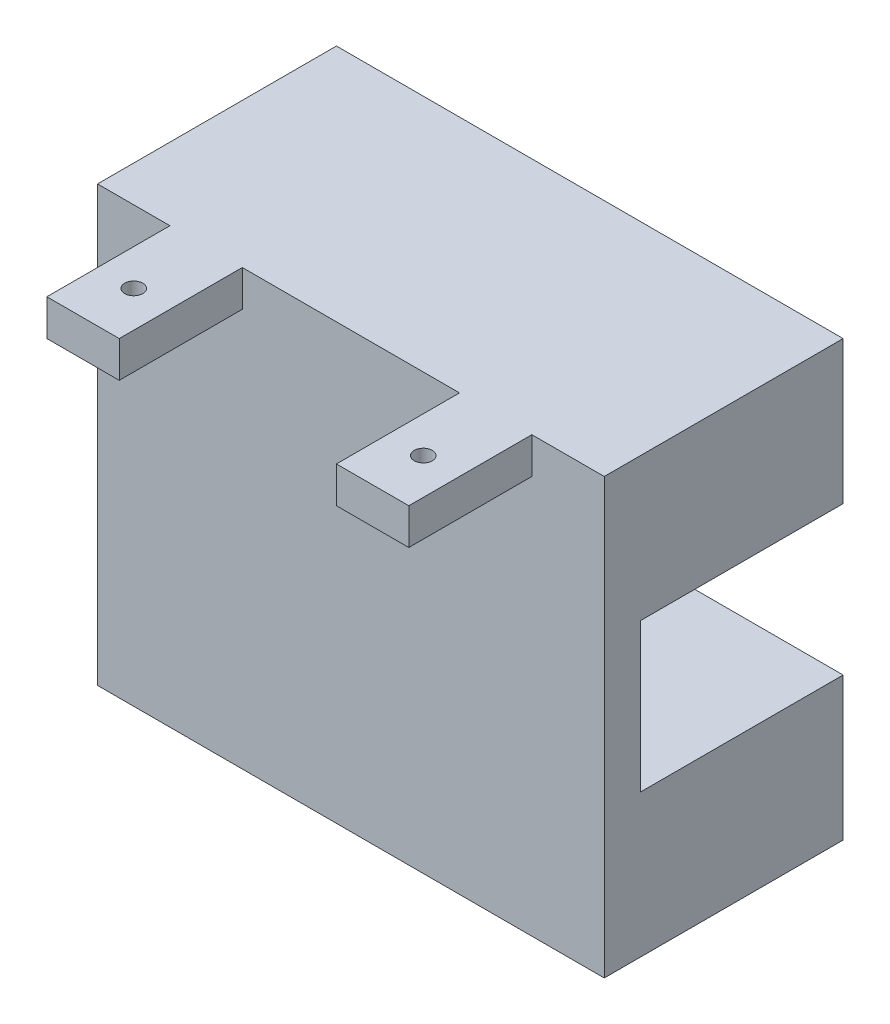
SolidWorks part; units mm, degrees
ref_plane "正面" through (0, 0, 0) normal (0, 0, 1) x (1, 0, 0)
ref_plane "平面" through (0, 0, 0) normal (0, 1, 0) x (1, 0, 0)
ref_plane "右側面" through (0, 0, 0) normal (1, 0, 0) x (0, 0, -1)
sketch "ｽｹｯﾁ2" plane through (0, 0, 0) normal (0, 0, 1) x (1, 0, 0)
  line L1 (-35, 30) -> (35, 30)
  line L2 (-35, 30) -> (-35, -30)
  line L3 (-35, -30) -> (35, -30)
  line L4 (35, 30) -> (35, -30)
  line L5 (-35, 30) -> (35, -30) construction
  line L6 (-35, -30) -> (35, 30) construction
  line L11 (-1.1602, 0.9945) -> (26.8884, -23.0472) construction
  line L12 (-15.8388, -9.5033) -> (15.8388, 9.5033) construction
  point P0 (0, 0)
  point P6 (0, 0)
  dimension "D1" = 70
  dimension "D2" = 60
extrude "ﾎﾞｽ - 押し出し2" add sketch "ｽｹｯﾁ2" along normal blind 33
sketch "ｽｹｯﾁ3" plane through (0, 0, 0) normal (0, 0, 1) x (1, 0, 0)
  line L1 (-20.35, 10.25) -> (20.35, 10.25)
  line L2 (-20.35, 10.25) -> (-20.35, -10.25)
  line L3 (-20.35, -10.25) -> (20.35, -10.25)
  line L4 (20.35, 10.25) -> (20.35, -10.25)
  line L5 (-20.35, 10.25) -> (20.35, -10.25) construction
  line L6 (-20.35, -10.25) -> (20.35, 10.25) construction
  point P0 (0, 0)
  dimension "D1" = 40.7
  dimension "D2" = 20.5
extrude "ｶｯﾄ - 押し出し1" cut sketch "ｽｹｯﾁ3" along normal blind 28 contours L2 L1 L4 L3
sketch "ｽｹｯﾁ4" plane through (0, 0, 0) normal (0, 0, 1) x (1, 0, 0)
  line L0 (20.35, 10.25) -> (35, 10.25)
  line L1 (35, -30) -> (35, 30) construction
  line L2 (35, 10.25) -> (35, -10.25)
  line L3 (35, -10.25) -> (20.35, -10.25)
  line L4 (20.35, -10.25) -> (20.35, 10.25)
extrude "ﾎﾞｽ - 押し出し3" add sketch "ｽｹｯﾁ4" along normal blind 28
sketch "ｽｹｯﾁ5" plane through (0, 0, 0) normal (0, 0, 1) x (1, 0, 0)
  line L0 (20.35, 10.25) -> (35, 10.25)
  line L1 (35, -30) -> (35, 30) construction
  line L2 (35, 10.25) -> (35, -10.25)
  line L3 (35, -10.25) -> (20.35, -10.25)
  line L4 (20.35, -10.25) -> (20.35, 10.25)
extrude "ｶｯﾄ - 押し出し4" cut sketch "ｽｹｯﾁ5" along normal blind 28
sketch "ｽｹｯﾁ6" plane through (0, 0, 0) normal (0, 0, 1) x (1, 0, 0)
  line L0 (-25, -30) -> (-25, -25)
  line L1 (-35, -30) -> (35, -30) construction
  line L2 (-25, -25) -> (-15, -25)
  line L3 (-15, -25) -> (-15, -30)
  line L4 (-15, -30) -> (-25, -30)
  line L5 (15, -25) -> (15, -30)
  line L6 (15, -30) -> (25, -30)
  line L7 (25, -30) -> (25, -25)
  line L8 (25, -25) -> (15, -25)
  dimension "D1" = 15
  dimension "D2" = 10
  dimension "D3" = 15
  dimension "D4" = 10
  dimension "D5" = 5
  dimension "D6" = 5
sketch "ｽｹｯﾁ8" plane through (0, 0, 0) normal (0, 0, 1) x (1, 0, 0)
  line L0 (-25, 30) -> (-25, 25)
  line L1 (35, 30) -> (-35, 30) construction
  line L2 (-25, 25) -> (-15, 25)
  line L3 (-15, 25) -> (-15, 30)
  line L4 (-15, 30) -> (-25, 30)
  line L5 (15, 30) -> (15, 25)
  line L6 (15, 25) -> (25, 25)
  line L7 (25, 25) -> (25, 30)
  line L8 (25, 30) -> (15, 30)
  dimension "D1" = 15
  dimension "D2" = 10
  dimension "D3" = 5
  dimension "D4" = 5
  dimension "D5" = 10
  dimension "D6" = 10
  dimension "D7" = 15
extrude "ﾎﾞｽ - 押し出し5" add sketch "ｽｹｯﾁ8" along normal blind 50
hole_wizard "M3x0.5 ねじ穴1" positions "ｽｹｯﾁ9" profile "ｽｹｯﾁ10" tap size "M3x0.5" standard "JIS" end condition through all
sketch "ｽｹｯﾁ9" plane through (0, 30, 0) normal (0, 1, 0) x (1, 0, 0)
  line L1 (15, -33) -> (-15, -33) construction
  line L2 (35, -33) -> (25, -33) construction
  point P0 (-20, -43)
  point P2 (20, -43)
  dimension "D1" = 10
  dimension "D2" = 10
  dimension "D3" = 20
  dimension "D4" = 20
sketch "ｽｹｯﾁ10" plane through (-20, 30, 43) normal (1, 0, 0) x (0, 0, 1)
  line L0 (0, 0) -> (0, 60)
  line L1 (0, 60) -> (1.25, 60)
  line L2 (1.25, 60) -> (1.25, 0)
  line L5 (1.25, 0) -> (0, 0)
  line L11 (0, -6.35) -> (0, 107.95) construction
  dimension "次ｻｰﾌｪｽまでのねじ下穴ﾄﾞﾘﾙ直径" = 2.5
  dimension "次ｻｰﾌｪｽまでのねじ下穴ﾄﾞﾘﾙの深さ" = 60
cosmetic thread "穴のねじ山1" parameters "D2"=3
cosmetic thread "穴のねじ山2" parameters "D2"=3
